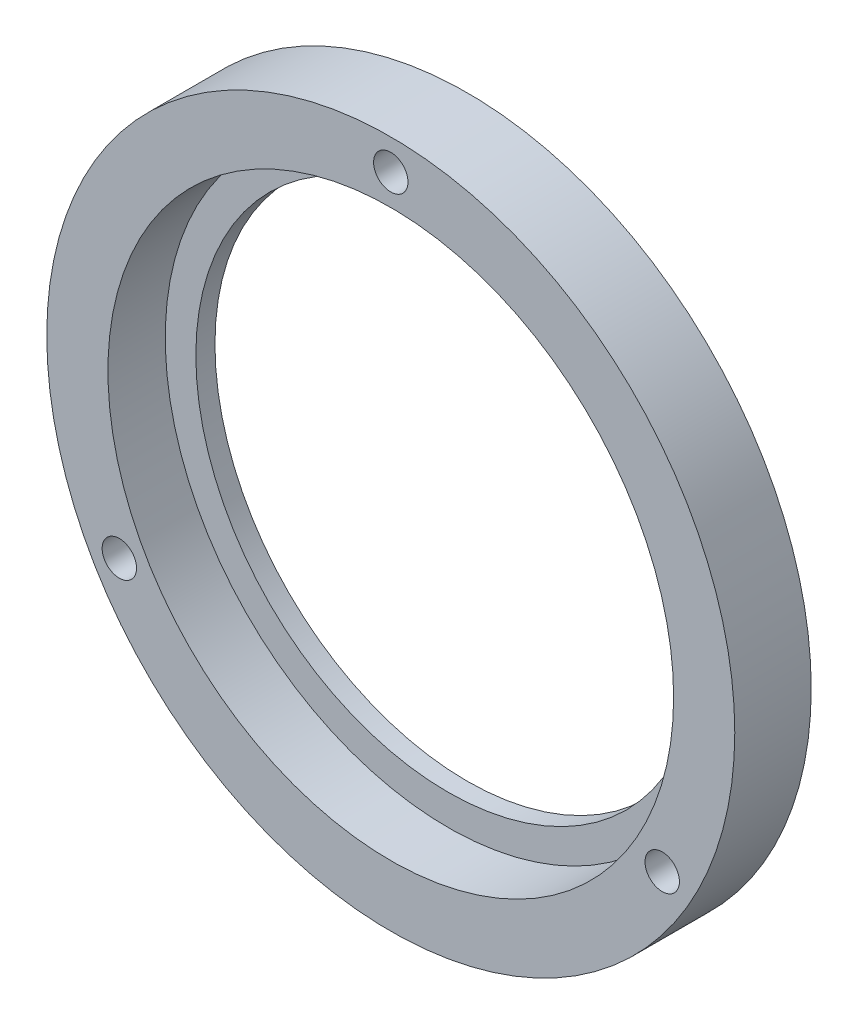
SolidWorks part; units mm, degrees
ref_plane "Plan1" through (0, 0, 0) normal (0, 0, 1) x (1, 0, 0)
ref_plane "Plan2" through (0, 0, 0) normal (0, 1, 0) x (1, 0, 0)
ref_plane "Plan3" through (0, 0, 0) normal (1, 0, 0) x (0, 0, -1)
sketch "Esquisse1" plane through (0, 0, 0) normal (0, 1, 0) x (1, 0, 0)
  line L0 (0, -30) -> (0, 40) construction
  line L1 (33, 10) -> (45, 10)
  line L2 (45, 10) -> (45, 0)
  line L3 (45, 0) -> (37, 0)
  line L4 (37, 0) -> (37, 7.5)
  line L5 (37, 7.5) -> (33, 7.5)
  line L6 (33, 7.5) -> (33, 10)
  dimension "D1" = 66
  dimension "D2" = 90
  dimension "D3" = 7.5
  dimension "D4" = 10
  dimension "D5" = 74
revolve "Base-Révolution" add sketch "Esquisse1" angle 360 about L0
sketch "Esquisse2" plane through (0, 0, 0) normal (0, 0, 1) x (1, 0, 0)
  line L0 (0, 0) -> (0, 45.4042) construction
  circle A0 centre (0, 0) radius 41 construction
  circle A1 centre (0, 41) radius 2.25
  dimension "D1" = 4.5
  dimension "D2" = 82
extrude "Enlèv. mat.-Extru.1" cut sketch "Esquisse2" against normal through all
pattern_circular "Répétition circulaire1" count 3 every 120 about axis through (0, 0, 0) along (0, 0, 1) of "Enlèv. mat.-Extru.1"
